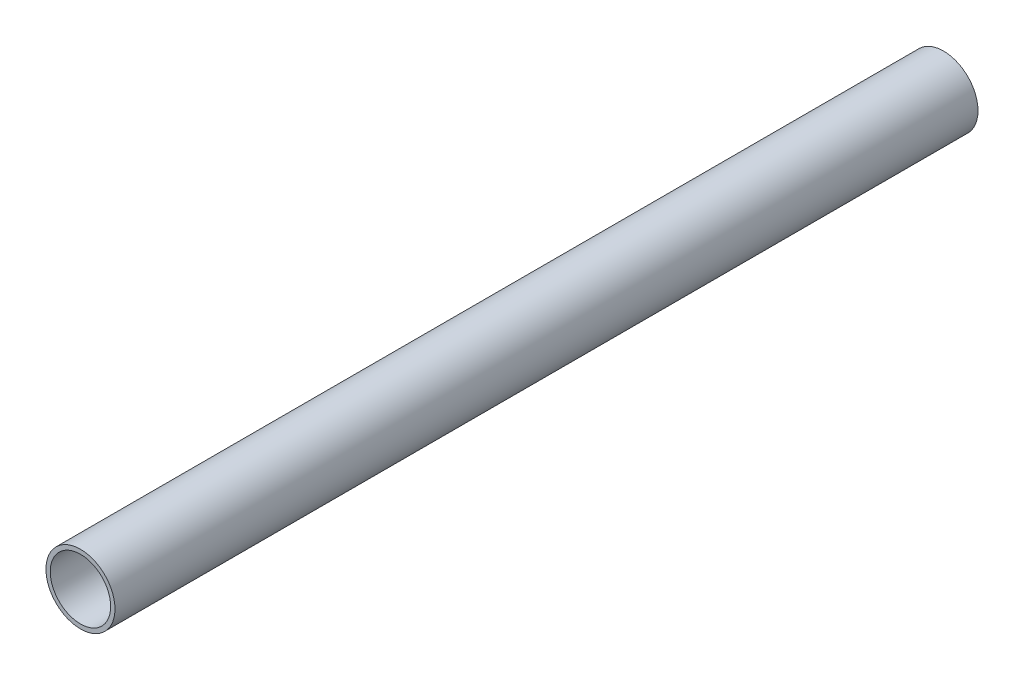
SolidWorks part; units mm, degrees
ref_plane "Ön Düzlem" through (0, 0, 0) normal (0, 0, 1) x (1, 0, 0)
ref_plane "Üst Düzlem" through (0, 0, 0) normal (0, 1, 0) x (1, 0, 0)
ref_plane "Sağ Düzlem" through (0, 0, 0) normal (1, 0, 0) x (0, 0, -1)
sketch "Çizim1" plane through (0, 0, 0) normal (0, 0, 1) x (1, 0, 0)
  circle A0 centre (0, 0) radius 7
  circle A1 centre (0, 0) radius 8
  dimension "D1" = 16
  dimension "D2" = 14
extrude "Yükseklik-Ekstrüzyon1" add sketch "Çizim1" along normal blind 200
